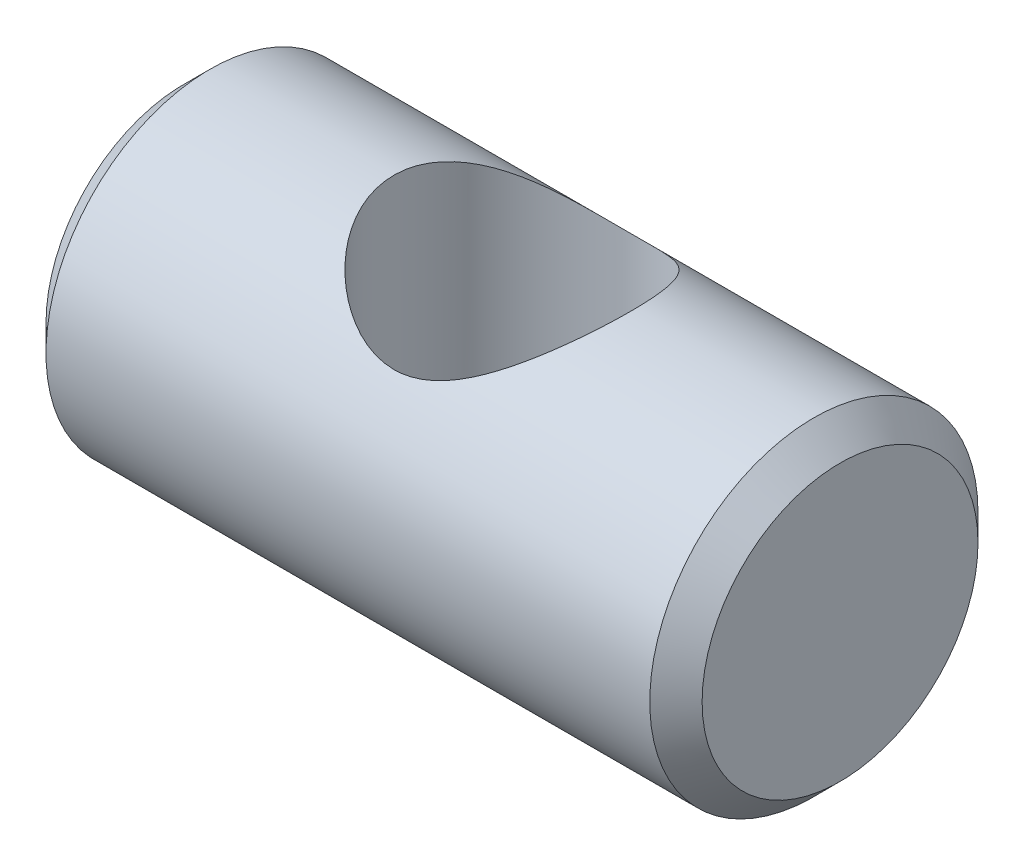
SolidWorks part; units mm, degrees
material "201 Annealed Stainless Steel (SS)"
ref_plane "Front Plane" through (0, 0, 0) normal (0, 0, 1) x (1, 0, 0)
ref_plane "Top Plane" through (0, 0, 0) normal (0, 1, 0) x (1, 0, 0)
ref_plane "Right Plane" through (0, 0, 0) normal (1, 0, 0) x (0, 0, -1)
sketch "Sketch1" plane through (0, 0, 0) normal (1, 0, 0) x (0, 0, -1)
  circle A0 centre (0, 0) radius 4.765
extrude "Boss-Extrude1" add sketch "Sketch1" along normal blind 19.05
chamfer "Chamfer1" distance 0.76 angle 45 2 edges at (0, 0, -4.765) (19.05, 0, -4.765)
sketch "Sketch2" plane through (0, 0, 0) normal (0, 1, 0) x (1, 0, 0)
  circle A0 centre (9.525, 0) radius 3.43
extrude "Cut-Extrude1" cut sketch "Sketch2" against normal through all both and the other way through all
